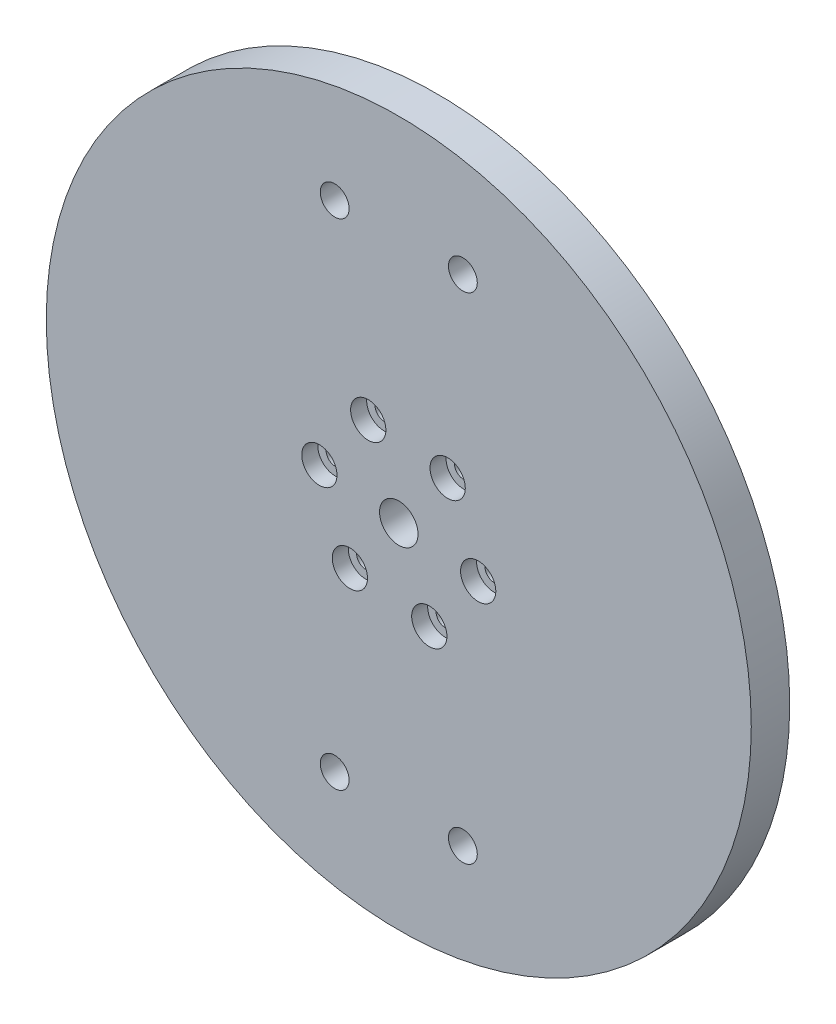
SolidWorks part; units mm, degrees
material "Aleación 6061"
ref_plane "Alzado" through (0, 0, 0) normal (0, 0, 1) x (1, 0, 0)
ref_plane "Planta" through (0, 0, 0) normal (0, 1, 0) x (1, 0, 0)
ref_plane "Vista lateral" through (0, 0, 0) normal (1, 0, 0) x (0, 0, -1)
sketch "Sk_Disco" plane through (0, 0, 0) normal (0, 0, 1) x (1, 0, 0)
  circle A0 centre (0, 0) radius 55
  dimension "D1" = 110
extrude "Disco" add sketch "Sk_Disco" along normal blind 6 from offset 420
sketch "Sk_Pasantes_M2-5_rotor_J4" plane through (0, 0, 0) normal (0, 0, 1) x (1, 0, 0)
  circle A0 centre (12.3902, -1.6532) radius 1.45
  circle A1 centre (7.6268, 9.9036) radius 1.45
  circle A2 centre (-4.7634, 11.5568) radius 1.45
  circle A3 centre (-12.3902, 1.6532) radius 1.45
  circle A4 centre (-7.6268, -9.9036) radius 1.45
  circle A5 centre (4.7634, -11.5568) radius 1.45
  dimension "D1" = 2.9
  dimension "D4" = 2.9
  dimension "D7" = 2.9
  dimension "D10" = 2.9
  dimension "D13" = 2.9
  dimension "D16" = 2.9
  dimension "D2" = 12.3902
  dimension "D3" = 1.6532
  dimension "D5" = 7.6268
  dimension "D6" = 9.9036
  dimension "D8" = 4.7634
  dimension "D9" = 11.5568
  dimension "D11" = 12.3902
  dimension "D12" = 1.6532
  dimension "D14" = 7.6268
  dimension "D15" = 9.9036
  dimension "D17" = 4.7634
  dimension "D18" = 11.5568
extrude "Pasantes_M2-5_rotor_J4" cut sketch "Sk_Pasantes_M2-5_rotor_J4" along normal blind 6 from offset 420
sketch "Sk_Cajas_M2-5" plane through (0, 0, 0) normal (0, 0, 1) x (1, 0, 0)
  circle A0 centre (12.3902, -1.6532) radius 2.75
  circle A1 centre (7.6268, 9.9036) radius 2.75
  circle A2 centre (-4.7634, 11.5568) radius 2.75
  circle A3 centre (-12.3902, 1.6532) radius 2.75
  circle A4 centre (-7.6268, -9.9036) radius 2.75
  circle A5 centre (4.7634, -11.5568) radius 2.75
  dimension "D1" = 5.5
  dimension "D4" = 5.5
  dimension "D7" = 5.5
  dimension "D10" = 5.5
  dimension "D13" = 5.5
  dimension "D16" = 5.5
  dimension "D2" = 12.3902
  dimension "D3" = 1.6532
  dimension "D5" = 7.6268
  dimension "D6" = 9.9036
  dimension "D8" = 4.7634
  dimension "D9" = 11.5568
  dimension "D11" = 12.3902
  dimension "D12" = 1.6532
  dimension "D14" = 7.6268
  dimension "D15" = 9.9036
  dimension "D17" = 4.7634
  dimension "D18" = 11.5568
extrude "Cajas_M2-5" cut sketch "Sk_Cajas_M2-5" along normal blind 2.5 from offset 423.5
sketch "Sk_Paso_cable" plane through (0, 0, 0) normal (0, 0, 1) x (1, 0, 0)
  circle A0 centre (0, 0) radius 3
  dimension "D1" = 6
extrude "Paso_cable" cut sketch "Sk_Paso_cable" along normal blind 6 from offset 420
sketch "Sk_Pasantes_M4_angulos" plane through (0, 0, 0) normal (0, 0, 1) x (1, 0, 0)
  circle A0 centre (-10, -38.61) radius 2.25
  circle A1 centre (-10, 38.61) radius 2.25
  circle A2 centre (10, -38.61) radius 2.25
  circle A3 centre (10, 38.61) radius 2.25
  dimension "D1" = 4.5
  dimension "D4" = 4.5
  dimension "D7" = 4.5
  dimension "D10" = 4.5
  dimension "D2" = 10
  dimension "D3" = 38.61
  dimension "D5" = 10
  dimension "D6" = 38.61
  dimension "D8" = 10
  dimension "D9" = 38.61
  dimension "D11" = 10
  dimension "D12" = 38.61
extrude "Pasantes_M4_angulos" cut sketch "Sk_Pasantes_M4_angulos" along normal blind 6 from offset 420
